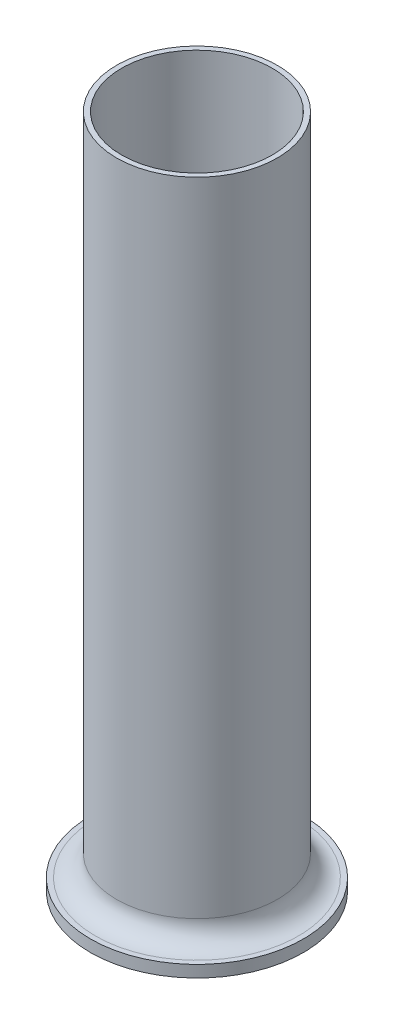
SolidWorks part; units mm, degrees
ref_plane "정면" through (0, 0, 0) normal (0, 0, 1) x (1, 0, 0)
ref_plane "윗면" through (0, 0, 0) normal (0, 1, 0) x (1, 0, 0)
ref_plane "우측면" through (0, 0, 0) normal (1, 0, 0) x (0, 0, -1)
sketch "스케치1" plane through (0, 0, 0) normal (0, 1, 0) x (1, 0, 0)
  circle A0 centre (0, 0) radius 25.25
  dimension "D1" = 50.5
extrude "보스-돌출1" add sketch "스케치1" along normal blind 2.8
sketch "스케치2" plane through (0, 2.8, 0) normal (0, 1, 0) x (1, 0, 0)
  circle A0 centre (0, 0) radius 19.05
  dimension "D1" = 38.1
extrude "보스-돌출2" add sketch "스케치2" along normal blind 157.2
fillet "필렛1" radius 5 1 edges at (0, 2.8, 19.05)
sketch "스케치3" plane through (0, 160, 0) normal (0, 1, 0) x (1, 0, 0)
  circle A0 centre (0, 0) radius 17.85
  dimension "D1" = 35.7
extrude "컷-돌출1" cut sketch "스케치3" against normal through all
sketch "스케치4" plane through (0, 0, 0) normal (0, -1, 0) x (1, 0, 0)
  circle A0 centre (0, 0) radius 21.75
  dimension "D1" = 43.5
sketch "스케치5" plane through (0, 0, 0) normal (0, 0, 1) x (1, 0, 0)
  line L0 (-21.75, 0) -> (21.75, 0) construction
  circle A0 centre (-21.75, 0) radius 1.8
  point P4 (-29.9559, 0)
  dimension "D2" = 3.6
  dimension "D1" = 21.75
sweep "컷-스윕1" cut profiles "스케치5" path "스케치4"
